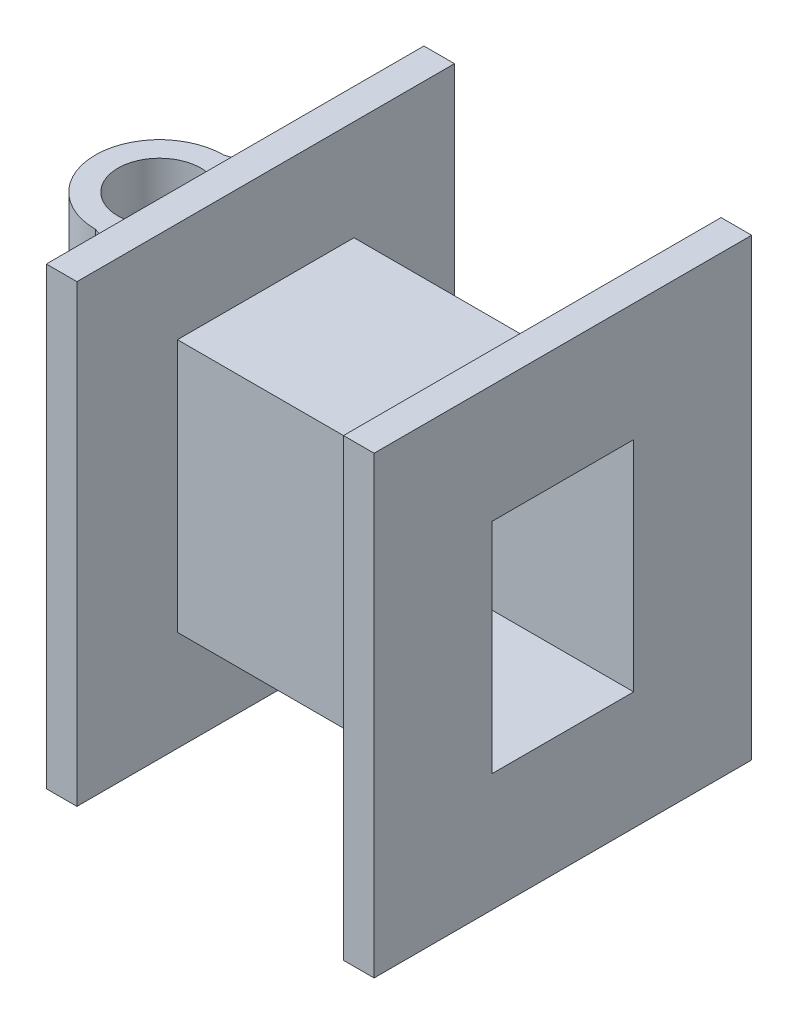
SolidWorks part; units mm, degrees
ref_plane "Front Plane" through (0, 0, 0) normal (0, 0, 1) x (1, 0, 0)
ref_plane "Top Plane" through (0, 0, 0) normal (0, 1, 0) x (1, 0, 0)
ref_plane "Right Plane" through (0, 0, 0) normal (1, 0, 0) x (0, 0, -1)
sketch "Sketch1" plane through (0, 0, 0) normal (1, 0, 0) x (0, 0, -1)
  line L0 (-10.1, 14.5) -> (-10.1, -14.5)
  line L1 (-8.1, 12.5) -> (8.1, 12.5)
  line L2 (-8.1, 12.5) -> (-8.1, -12.5)
  line L3 (-8.1, -12.5) -> (8.1, -12.5)
  line L4 (8.1, 12.5) -> (8.1, -12.5)
  line L5 (-8.1, 12.5) -> (8.1, -12.5) construction
  line L6 (-8.1, -12.5) -> (8.1, 12.5) construction
  line L7 (-10.1, -14.5) -> (10.1, -14.5)
  line L8 (10.1, 14.5) -> (10.1, -14.5)
  line L9 (-10.1, 14.5) -> (10.1, 14.5)
  point P0 (0, 0)
  dimension "D1" = 25
  dimension "D2" = 16.2
  dimension "D3" = 2
extrude "Boss-Extrude1" add sketch "Sketch1" along normal mid plane 37.5
sketch "Sketch2" plane through (0, 14.5, 0) normal (0, 1, 0) x (1, 0, 0)
  line L8 (-18.75, -10.1) -> (-18.75, 10.1)
  line L10 (-18.75, -10.1) -> (-27.403, -7.347)
  line L11 (-18.75, 10.1) -> (-27.403, 7.347)
  arc A0 (-27.403, 7.347) -> (-27.403, -7.347) centre (-27.403, 0) ccw
  circle A1 centre (-27.403, 0) radius 4.75
  point P2 (-27.403, 0)
  dimension "D1" = 9.5
extrude "Boss-Extrude2" add sketch "Sketch2" against normal blind 2 and the other way blind 3.5
sketch "Sketch3" plane through (18.75, 0, 0) normal (1, 0, 0) x (0, 0, -1)
  line L0 (-10.1, 14.5) -> (-10.1, -14.5) construction
  line L1 (-21.6, 26) -> (21.6, 26)
  line L2 (-21.6, 26) -> (-21.6, -26)
  line L3 (-21.6, -26) -> (21.6, -26)
  line L4 (21.6, 26) -> (21.6, -26)
  line L5 (-21.6, 26) -> (21.6, -26) construction
  line L6 (-21.6, -26) -> (21.6, 26) construction
  line L7 (10.1, 14.5) -> (-10.1, 14.5) construction
  line L9 (-8.1, -12.5) -> (8.1, -12.5)
  line L10 (-8.1, -12.5) -> (-8.1, 12.5)
  line L11 (-8.1, 12.5) -> (8.1, 12.5)
  line L12 (8.1, -12.5) -> (8.1, 12.5)
  line L13 (-8.1, -12.5) -> (8.1, 12.5) construction
  line L14 (-8.1, 12.5) -> (8.1, -12.5) construction
  point P0 (0, 0)
  point P10 (0, 0)
  dimension "D1" = 11.5
  dimension "D2" = 11.5
extrude "Boss-Extrude4" add sketch "Sketch3" against normal blind 3.5
mirror "Mirror1" about plane through (0, 0, 0) normal (1, 0, 0) of "Boss-Extrude4"
